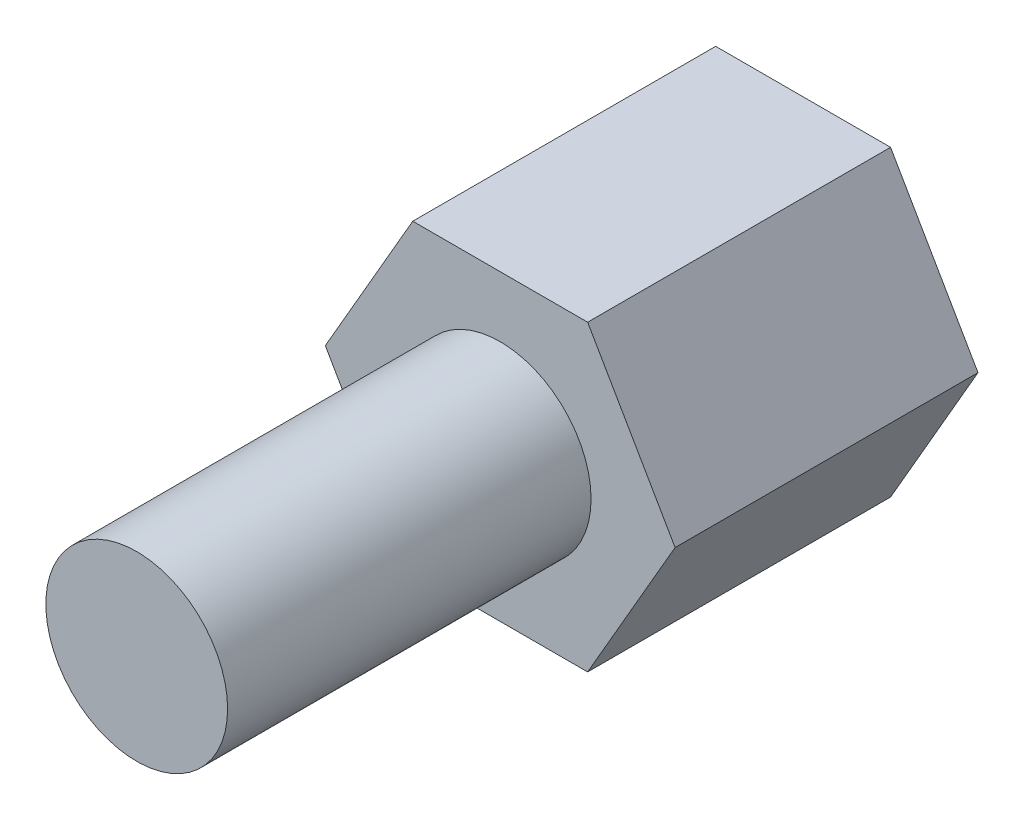
SolidWorks part; units mm, degrees
ref_plane "前视基准面" through (0, 0, 0) normal (0, 0, 1) x (1, 0, 0)
ref_plane "上视基准面" through (0, 0, 0) normal (0, 1, 0) x (1, 0, 0)
ref_plane "右视基准面" through (0, 0, 0) normal (1, 0, 0) x (0, 0, -1)
sketch "草图1" plane through (0, 0, 0) normal (0, 0, 1) x (1, 0, 0)
  line L0 (-28.6627, 0) -> (33.6774, 0) construction
  line L1 (1.4434, -2.5) -> (2.8868, 0)
  line L2 (2.8868, 0) -> (1.4434, 2.5)
  line L3 (1.4434, 2.5) -> (-1.4434, 2.5)
  line L4 (-1.4434, 2.5) -> (-2.8868, 0)
  line L5 (-2.8868, 0) -> (-1.4434, -2.5)
  line L6 (-1.4434, -2.5) -> (1.4434, -2.5)
  circle A0 centre (0, 0) radius 2.5 construction
  dimension "D1" = 5
extrude "拉伸1" add sketch "草图1" along normal blind 5
sketch "草图2" plane through (0, 0, 5) normal (0, 0, 1) x (1, 0, 0)
  circle A0 centre (0, 0) radius 1.5
  dimension "D1" = 3
extrude "拉伸2" add sketch "草图2" along normal blind 6
hole_wizard "M3x0.5 螺纹孔1" positions "3D草图2" profile "草图5" tap size "M3x0.5" standard "ISO"
sketch3d "3D草图2"
  point P0 (0, 0, 0)
  point P2 (0, 0, 0)
  point P3 (0, 0, 0)
  point P4 (0, 0, 0)
cosmetic thread "孔螺蚊线1" parameters "D1"=4, "D2"=3
sketch "草图5" plane through (0, 0, 0) normal (1, 0, 0) x (0, 1, 0)
  line L0 (0, 0) -> (0, 7.2511)
  line L1 (0, 7.2511) -> (1.25, 6.5)
  line L2 (1.25, 6.5) -> (1.25, 0)
  line L5 (1.25, 0) -> (0, 0)
  line L10 (0, 7.2511) -> (-1.25, 6.5) construction
  line L11 (0, -6.35) -> (0, 107.95) construction
  dimension "蹟恇謂郰芛眻噤" = 2.5
  dimension "蹟恇謂郰芛旮僅" = 6.5
  dimension "絳芛褒僅" = 118
cosmetic thread "孔螺蚊线2" parameters "D1"=4, "D2"=3
cosmetic thread "孔螺蚊线3" parameters "D1"=4, "D2"=3
cosmetic thread "孔螺蚊线4" parameters "D1"=4, "D2"=3
sketch "草图6" plane through (0, 0, 0) normal (0, 0, -1) x (-1, 0, 0)
  circle A0 centre (0, 0) radius 1.5
  dimension "D1" = 3
extrude "拉伸3" add sketch "草图6" along normal blind 10
